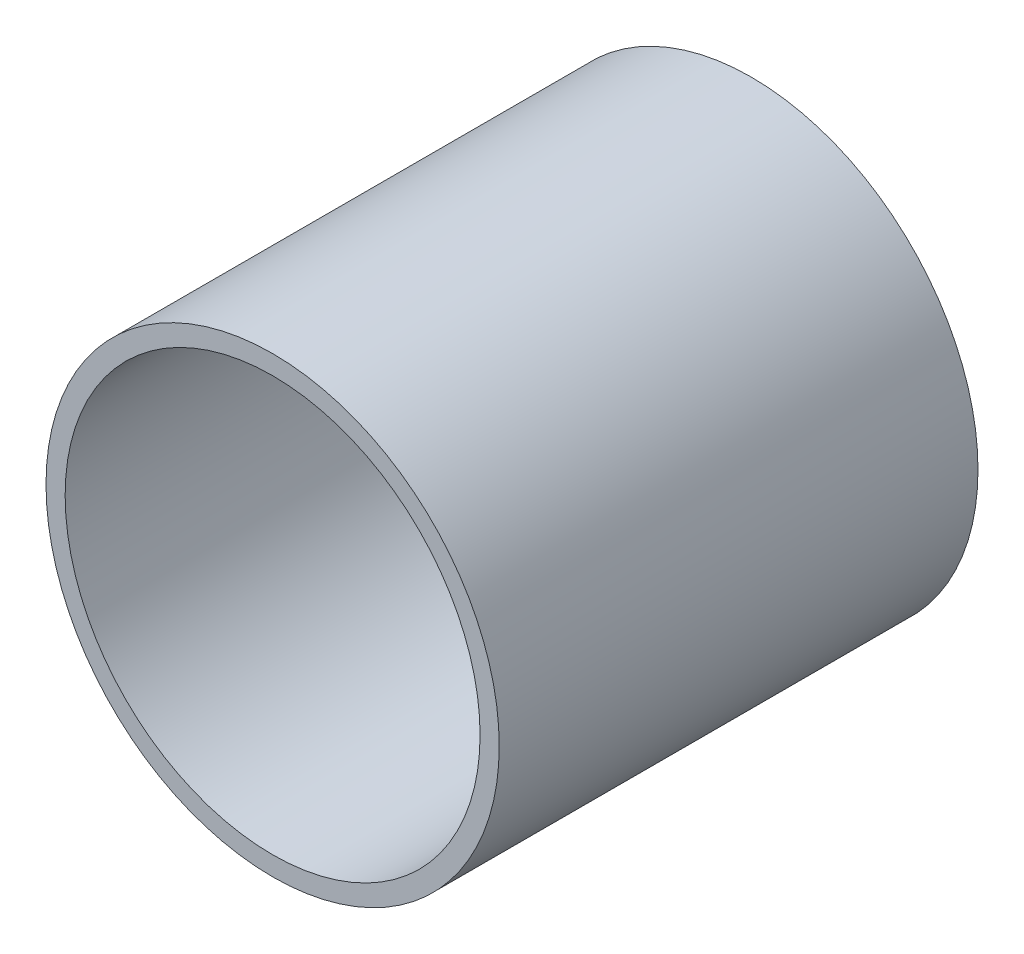
SolidWorks part; units mm, degrees
ref_plane "Plan de face" through (0, 0, 0) normal (0, 0, 1) x (1, 0, 0)
ref_plane "Plan de dessus" through (0, 0, 0) normal (0, 1, 0) x (1, 0, 0)
ref_plane "Plan de droite" through (0, 0, 0) normal (1, 0, 0) x (0, 0, -1)
sketch "Esquisse1" plane through (0, 0, 0) normal (0, 0, 1) x (1, 0, 0)
  circle A0 centre (0, 0) radius 32.5
  circle A1 centre (0, 0) radius 35.5
  dimension "D1" = 65
  dimension "D2" = 71
extrude "Boss.-Extru.1" add sketch "Esquisse1" along normal blind 75
